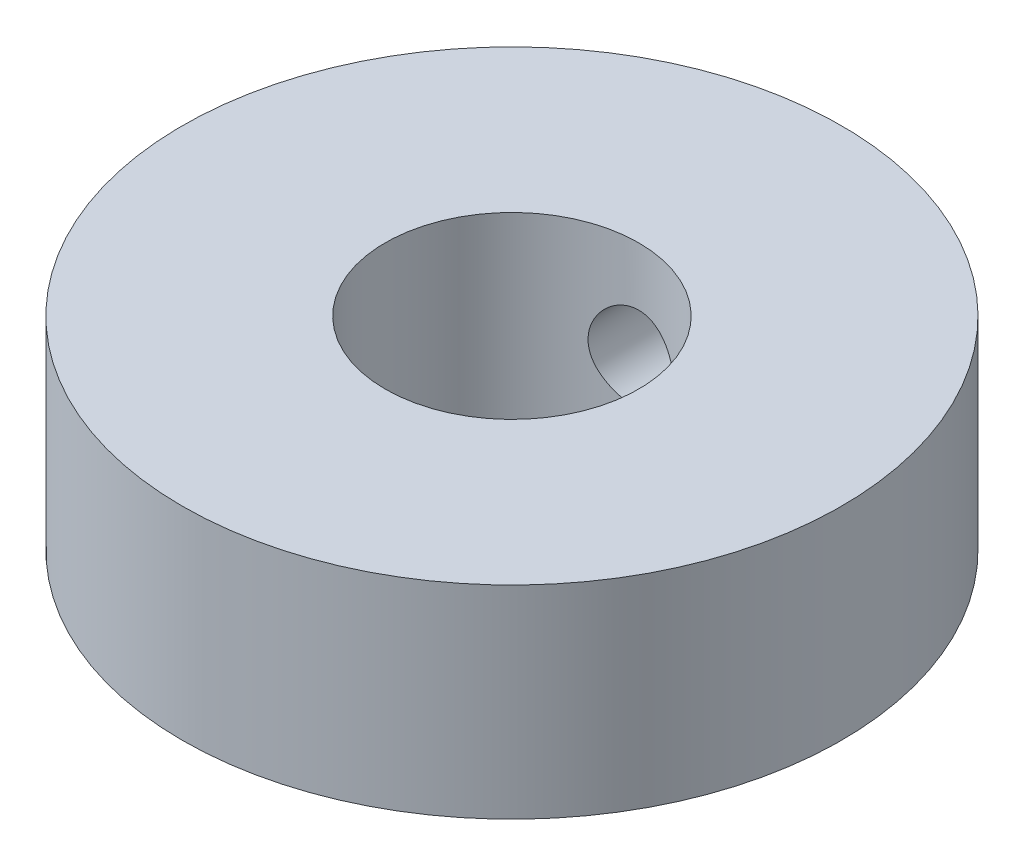
SolidWorks part; units mm, degrees
ref_plane "Front Plane" through (0, 0, 0) normal (0, 0, 1) x (1, 0, 0)
ref_plane "Top Plane" through (0, 0, 0) normal (0, 1, 0) x (1, 0, 0)
ref_plane "Right Plane" through (0, 0, 0) normal (1, 0, 0) x (0, 0, -1)
sketch "Sketch1" plane through (0, 0, 0) normal (0, 1, 0) x (1, 0, 0)
  circle A0 centre (0, 0) radius 6.5
  dimension "D1" = 13
extrude "Boss-Extrude1" add sketch "Sketch1" along normal blind 4
sketch "Sketch2" plane through (0, 4, 0) normal (0, 1, 0) x (1, 0, 0)
  circle A0 centre (0, 0) radius 2.5
  dimension "D1" = 5
extrude "Cut-Extrude1" cut sketch "Sketch2" against normal through all
sketch "Sketch3" plane through (0, 0, 0) normal (0, 0, 1) x (1, 0, 0)
  line L0 (0, 4) -> (0, 0) construction
  line L1 (2.5, 4) -> (-2.5, 4) construction
  circle A0 centre (0, 2) radius 0.85
  dimension "D1" = 1.7
  dimension "D2" = 2
extrude "Cut-Extrude2" cut sketch "Sketch3" against normal through all
